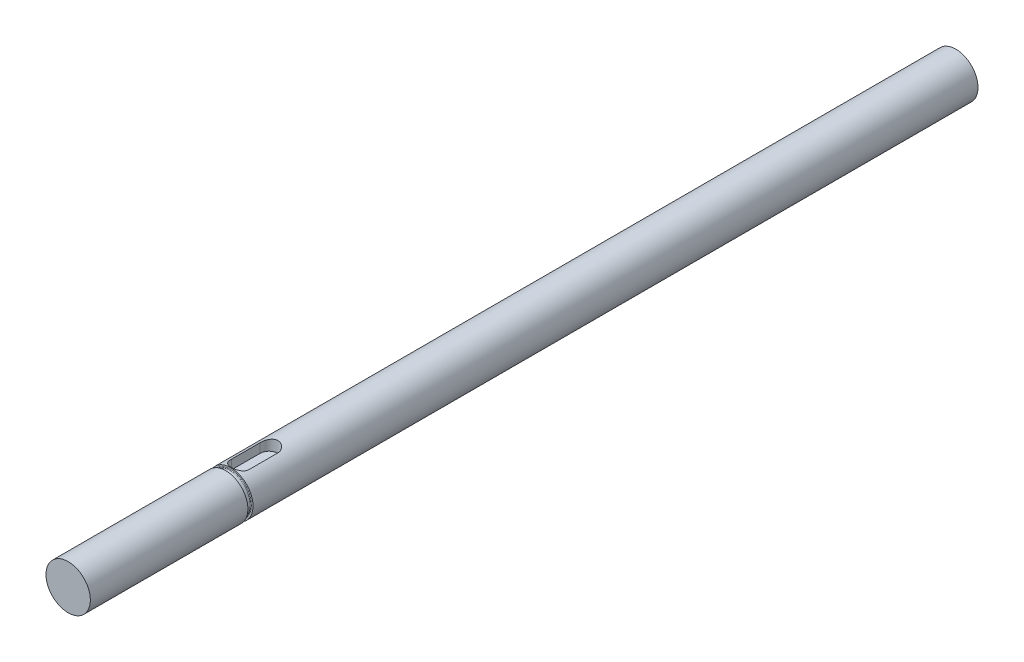
SolidWorks part; units mm, degrees
material "6061-O (SS)"
ref_plane "Alzado" through (0, 0, 0) normal (0, 0, 1) x (1, 0, 0)
ref_plane "Planta" through (0, 0, 0) normal (0, 1, 0) x (1, 0, 0)
ref_plane "Vista lateral" through (0, 0, 0) normal (1, 0, 0) x (0, 0, -1)
sketch "Croquis1" plane through (0, 0, 0) normal (0, 0, 1) x (1, 0, 0)
  circle A0 centre (0, 0) radius 5
  dimension "D1" = 10
extrude "Saliente-Extruir1" add sketch "Croquis1" along normal mid plane 200
sketch "Croquis2" plane through (0, 0, 0) normal (0, 1, 0) x (1, 0, 0)
  line L0 (0, -54.75) -> (0, -61.25) construction
  line L1 (2, -54.75) -> (2, -61.25)
  line L2 (-2, -54.75) -> (-2, -61.25)
  arc A0 (2, -54.75) -> (-2, -54.75) centre (0, -54.75) ccw
  arc A1 (-2, -61.25) -> (2, -61.25) centre (0, -61.25) ccw
  point P2 (0, -58)
  point P7 (0, -63.25)
  point P8 (0, -52.75)
  dimension "D1" = 4
  dimension "D2" = 10.5
  dimension "D3" = 58
extrude "Cortar-Extruir1" cut sketch "Croquis2" along normal through all from offset 2.5
ref_plane "Plano1" through (0, 0, 100) normal (-1, 0, 0) x (0, 1, 0)
sketch "Croquis4" plane through (0, 0, 100) normal (-1, 0, 0) x (0, 1, 0)
  line L0 (4.65, 35.5) -> (6.6414, 35.5)
  line L1 (6.6414, 35.5) -> (6.6414, 36.65)
  line L2 (6.6414, 36.65) -> (4.65, 36.65)
  line L3 (4.5, 36.5) -> (4.5, 35.65)
  line L4 (0, -50) -> (0, 50.8213) construction
  line L5 (-5, 0) -> (5, 0) construction
  arc A0 (4.5, 35.65) -> (4.65, 35.5) centre (4.65, 35.65) ccw
  arc A1 (4.5, 36.5) -> (4.65, 36.65) centre (4.65, 36.5) cw
  dimension "D1" = 0.15
  dimension "D2" = 0.15
  dimension "D3" = 35.5
  dimension "D4" = 1.15
  dimension "D5" = 4.5
revolve "Ranura para arandela de seguridad para ejes DIN 6799 - 91" cut sketch "Croquis4"
